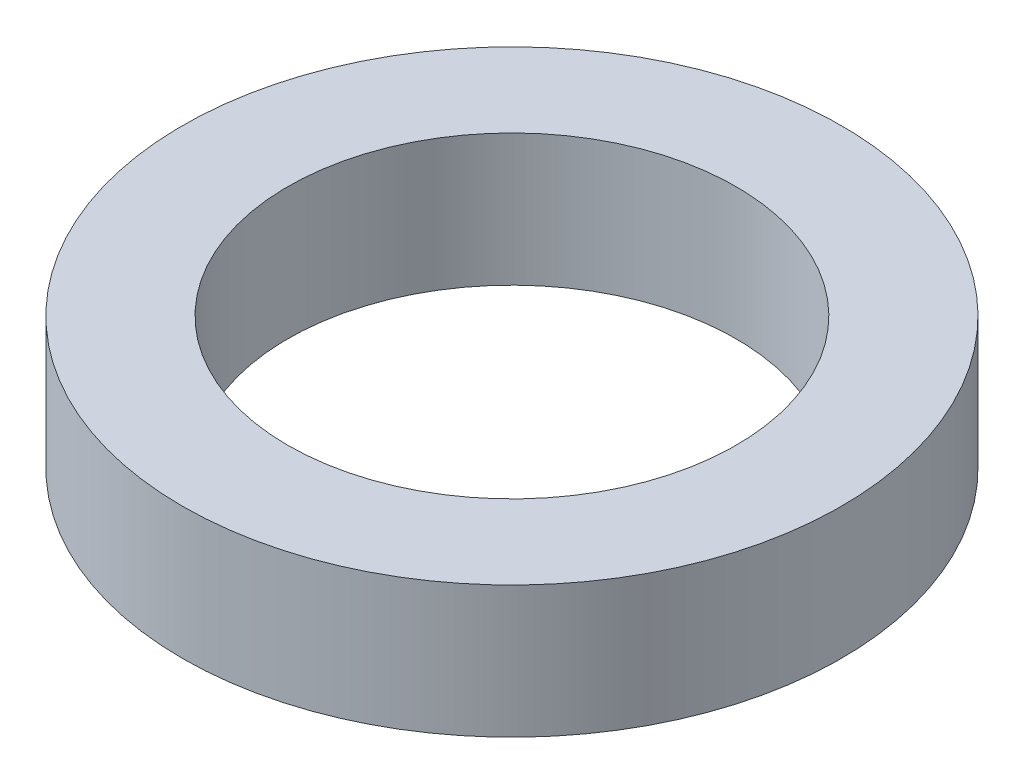
SolidWorks part; units mm, degrees
ref_plane "Plan de face" through (0, 0, 0) normal (0, 0, 1) x (1, 0, 0)
ref_plane "Plan de dessus" through (0, 0, 0) normal (0, 1, 0) x (1, 0, 0)
ref_plane "Plan de droite" through (0, 0, 0) normal (1, 0, 0) x (0, 0, -1)
sketch "Esquisse1" plane through (0, 0, 0) normal (0, 1, 0) x (1, 0, 0)
  circle A0 centre (0, 0) radius 8.5
  circle A1 centre (0, 0) radius 12.5
  dimension "D1" = 25
  dimension "D2" = 17
extrude "Boss.-Extru.1" add sketch "Esquisse1" along normal blind 5
